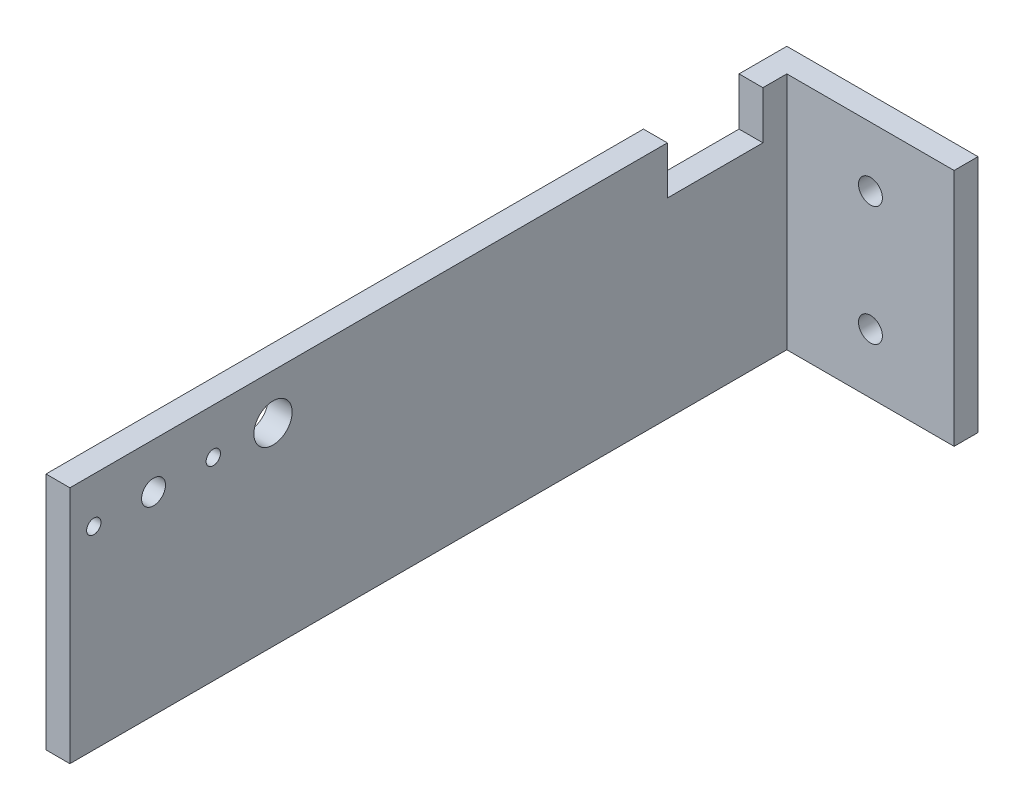
SolidWorks part; units mm, degrees
ref_plane "Front Plane" through (0, 0, 0) normal (0, 0, 1) x (1, 0, 0)
ref_plane "Top Plane" through (0, 0, 0) normal (0, 1, 0) x (1, 0, 0)
ref_plane "Right Plane" through (0, 0, 0) normal (1, 0, 0) x (0, 0, -1)
sketch "Sketch4" plane through (0, 0, 0) normal (0, 1, 0) x (1, 0, 0)
  line L0 (0, 0) -> (5, 0)
  line L1 (5, 0) -> (5, 150)
  line L2 (5, 150) -> (40, 150)
  line L3 (40, 150) -> (40, 155)
  line L4 (40, 155) -> (0, 155)
  line L5 (0, 155) -> (0, 0)
  dimension "D1" = 155
  dimension "D2" = 5
  dimension "D3" = 5
  dimension "D4" = 40
extrude "Boss-Extrude5" add sketch "Sketch4" along normal mid plane 50
sketch "Sketch6" plane through (5, 0, 0) normal (1, 0, 0) x (0, 0, -1)
  line L0 (0, 25) -> (0, -25) construction
  line L1 (17.5, 15.5) -> (17.5, 16.4605) construction
  line L2 (0, 25) -> (150, 25) construction
  line L3 (125, 25) -> (125, 15)
  line L4 (125, 15) -> (145, 15)
  line L5 (145, 15) -> (145, 25)
  line L6 (145, 25) -> (125, 25)
  line L7 (155, 25) -> (155, -25) construction
  circle A0 centre (5, 15.5) radius 1.5
  circle A1 centre (17.5, 15.5) radius 2.5
  circle A2 centre (30, 15.5) radius 1.5
  circle A3 centre (42.5, 15.5) radius 4
  dimension "D1" = 3
  dimension "D2" = 5
  dimension "D3" = 5
  dimension "D7" = 8
  dimension "D4" = 25
  dimension "D5" = 9.5
  dimension "D6" = 25
  dimension "D8" = 30
  dimension "D9" = 20
  dimension "D10" = 10
extrude "Cut-Extrude2" cut sketch "Sketch6" against normal up to next
sketch "Sketch1" plane through (0, 0, 0) normal (0, 0, 1) x (1, 0, 0)
  line L0 (0, 342) -> (0, 0)
  line L1 (0, 0) -> (40, 0)
  line L2 (40, 0) -> (40, 4)
  line L3 (40, 4) -> (4, 4)
  line L4 (4, 4) -> (4, 342)
  line L5 (4, 342) -> (0, 342)
  dimension "D1" = 342
  dimension "D2" = 4
  dimension "D3" = 4
  dimension "D4" = 40
extrude "Boss-Extrude1" [suppressed] add sketch "Sketch1" along normal mid plane 50
sketch "Sketch2" [suppressed] plane through (4, 0, 0) normal (1, 0, 0) x (0, 0, -1)
  line L0 (-25, 4) -> (-25, 342) construction
  line L1 (-25, 342) -> (25, 342) construction
  line L3 (-7.5, 332.5) -> (-7.5, 104.2032) construction
  circle A0 centre (-20, 332.5) radius 1.5
  circle A1 centre (5, 332.5) radius 1.5
  circle A2 centre (-7.5, 332.5) radius 2.5
  circle A3 centre (17.5, 332.5) radius 4
  dimension "D1" = 3
  dimension "D4" = 5
  dimension "D5" = 8
  dimension "D2" = 25
  dimension "D3" = 5
  dimension "D6" = 25
  dimension "D7" = 9.5
extrude "Cut-Extrude1" [suppressed] cut sketch "Sketch2" against normal up to next
sketch "Sketch7" plane through (0, 0, -150) normal (0, 0, 1) x (1, 0, 0)
  line L0 (0, 0) -> (38.9105, 0) construction
  line L1 (40, 25) -> (40, -25) construction
  circle A0 centre (22.5, 12.5) radius 2.5
  circle A1 centre (22.5, -12.5) radius 2.5
  dimension "D2" = 5
  dimension "D1" = 17.5
  dimension "D3" = 25
extrude "Cut-Extrude3" cut sketch "Sketch7" against normal up to next
